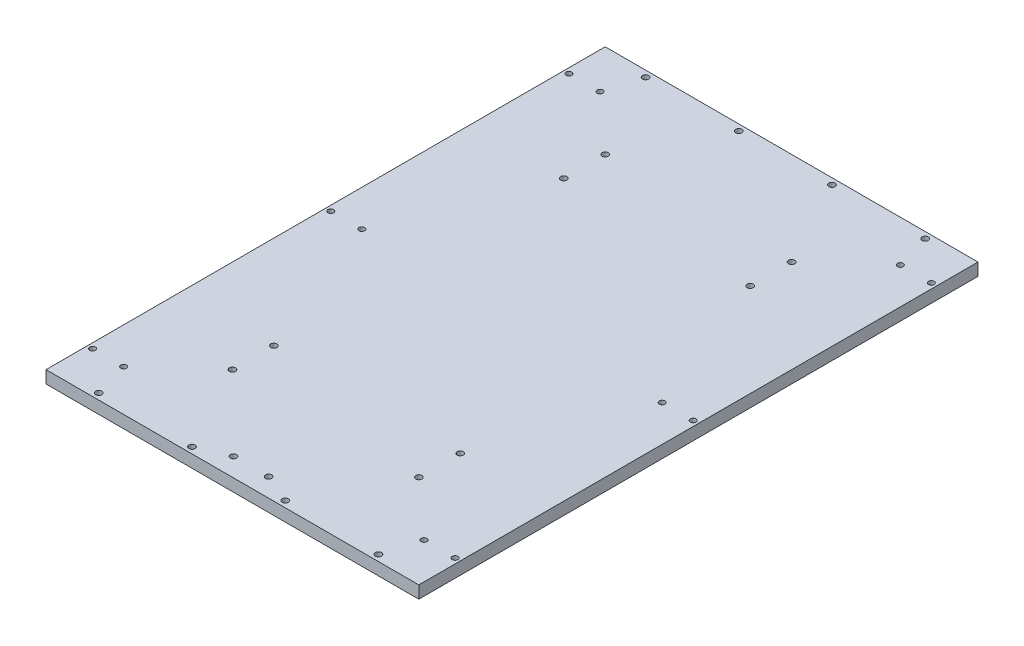
SolidWorks part; units mm, degrees
material "Beech"
ref_plane "Front Plane" through (0, 0, 0) normal (0, 0, 1) x (1, 0, 0)
ref_plane "Top Plane" through (0, 0, 0) normal (0, 1, 0) x (1, 0, 0)
ref_plane "Right Plane" through (0, 0, 0) normal (1, 0, 0) x (0, 0, -1)
sketch "Sketch1" plane through (0, 0, 0) normal (0, 1, 0) x (1, 0, 0)
  line L1 (-180, -270) -> (180, -270)
  line L2 (-180, -270) -> (-180, 270)
  line L3 (-180, 270) -> (180, 270)
  line L4 (180, -270) -> (180, 270)
  line L5 (-180, -270) -> (180, 270) construction
  line L6 (-180, 270) -> (180, -270) construction
  point P0 (0, 0)
extrude "Boss-Extrude1" add sketch "Sketch1" along normal blind 12
sketch "Sketch2" plane through (0, 0, 0) normal (0, -1, 0) x (1, 0, 0)
  line L0 (-197.9035, 252) -> (209.2572, 252) construction
  line L1 (-180, 270) -> (180, 270) construction
  line L2 (0, 285.6833) -> (0, -295.2195) construction
  circle A0 centre (-17, 252) radius 3
  circle A1 centre (17, 252) radius 3
  dimension "D2" = 6
  dimension "D3" = 6
  dimension "D4" = 34
  dimension "D5" = 17
  dimension "D1" = 18
extrude "Cut-Extrude1" cut sketch "Sketch2" against normal up to next
sketch "Sketch3" plane through (0, 0, 0) normal (0, -1, 0) x (1, 0, 0)
  line L0 (-207.4551, 264) -> (223.7581, 264) construction
  line L1 (-180, 270) -> (180, 270) construction
  line L2 (180, 270) -> (180, -270) construction
  circle A0 centre (135, 264) radius 3
  dimension "D2" = 6
  dimension "D3" = 45
  dimension "D1" = 6
extrude "Cut-Extrude2" cut sketch "Sketch3" against normal up to next
pattern_linear "LPattern1" count 4 spacing 90 along (-1, 0, 0) of "Cut-Extrude2"
mirror "Mirror1" about plane through (0, 0, 0) normal (0, 0, 1) of "LPattern1", "Cut-Extrude2"
sketch "Sketch4" plane through (0, 12, 0) normal (0, 1, 0) x (1, 0, 0)
  line L0 (-160, 299.1839) -> (-160, -309.0635) construction
  line L1 (-180, 270) -> (-180, -270) construction
  line L2 (-188.5351, 0) -> (-124.846, 0) construction
  line L3 (-188.5351, 230) -> (-124.846, 230) construction
  line L4 (-129.91, -230) -> (-208.5429, -230) construction
  circle A0 centre (-175, 230) radius 2.75
  circle A1 centre (-145, 230) radius 2.75
  dimension "D4" = 5.5
  dimension "D5" = 5.5
  dimension "D7" = 15
  dimension "D1" = 20
  dimension "D2" = 230
  dimension "D3" = 230
  dimension "D6" = 15
extrude "Cut-Extrude3" cut sketch "Sketch4" against normal up to next
pattern_linear "LPattern2" count 3 spacing 230 along (0, 0, 1) of "Cut-Extrude3"
mirror "Mirror2" about plane through (0, 0, 0) normal (1, 0, 0) of "LPattern2", "Cut-Extrude3"
sketch "Sketch6" plane through (0, 12, 0) normal (0, 1, 0) x (1, 0, 0)
  line L0 (180, 270) -> (-180, 270) construction
  line L1 (-180, 270) -> (-180, -270) construction
  circle A0 centre (-90, 180) radius 3
  circle A1 centre (-90, 140) radius 3
  dimension "D1" = 6
  dimension "D2" = 6
  dimension "D3" = 90
  dimension "D4" = 90
  dimension "D5" = 40
  dimension "D6" = 90
extrude "Cut-Extrude4" cut sketch "Sketch6" against normal up to next
mirror "Mirror3" about plane through (0, 0, 0) normal (0, 0, 1) of "Cut-Extrude4"
mirror "Mirror4" about plane through (0, 0, 0) normal (1, 0, 0) of "Mirror3", "Cut-Extrude4"
